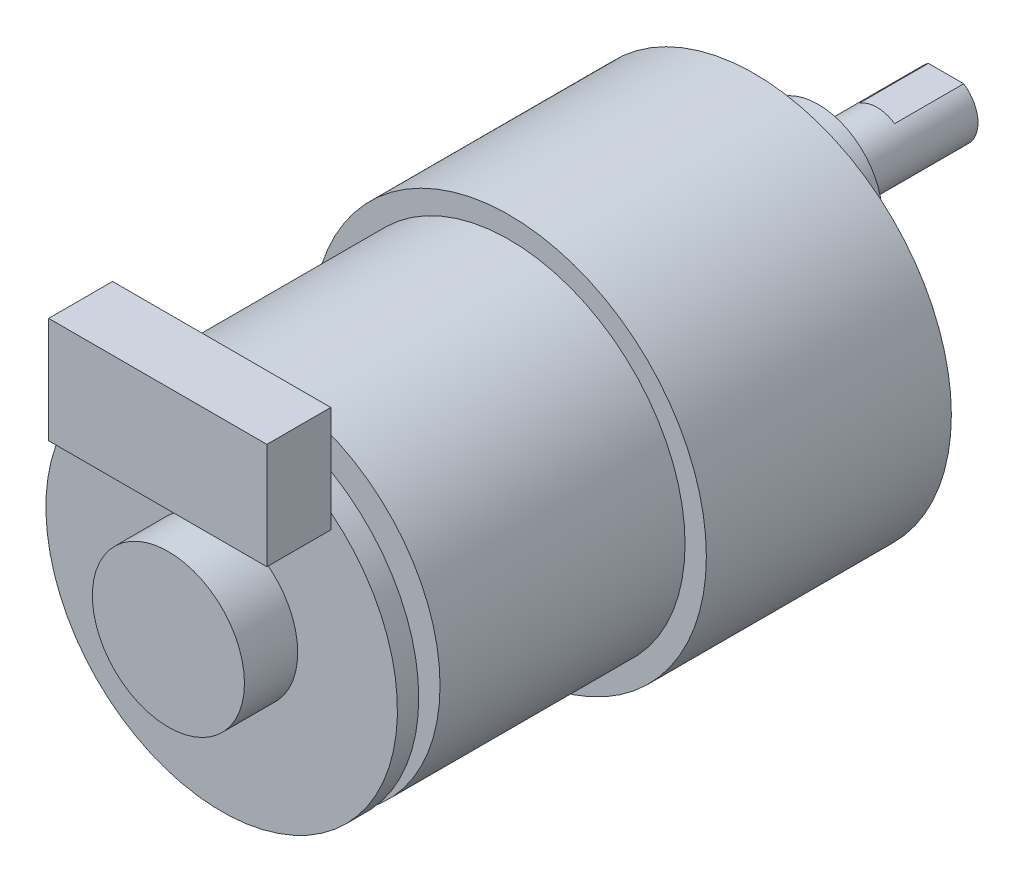
SolidWorks part; units mm, degrees
ref_plane "前视基准面" through (0, 0, 0) normal (0, 0, 1) x (1, 0, 0)
ref_plane "上视基准面" through (0, 0, 0) normal (0, 1, 0) x (1, 0, 0)
ref_plane "右视基准面" through (0, 0, 0) normal (1, 0, 0) x (0, 0, -1)
sketch "草图1" plane through (0, 0, 0) normal (0, 0, 1) x (1, 0, 0)
  circle A0 centre (0, 0) radius 18.5
  dimension "D1" = 37
extrude "凸台-拉伸1" add sketch "草图1" along normal blind 23
sketch "草图2" plane through (0, 0, 23) normal (0, 0, 1) x (1, 0, 0)
  circle A0 centre (0, 0) radius 16.5
  dimension "D1" = 33
extrude "凸台-拉伸2" add sketch "草图2" along normal blind 23
sketch "草图3" plane through (0, 0, 0) normal (0, 0, -1) x (-1, 0, 0)
  line L0 (-20.8009, 0) -> (22.2643, 0) construction
  circle A0 centre (0, 7) radius 6
  dimension "D1" = 12
  dimension "D2" = 7
extrude "凸台-拉伸3" add sketch "草图3" along normal blind 6
sketch "草图4" plane through (0, 0, -6) normal (0, 0, -1) x (-1, 0, 0)
  circle A0 centre (0, 7) radius 3
  dimension "D1" = 6
extrude "凸台-拉伸4" add sketch "草图4" along normal blind 12
sketch "草图5" plane through (0, 0, 0) normal (1, 0, 0) x (0, 0, -1)
  line L0 (6, 4) -> (18, 4) construction
  line L1 (11.5145, 19.9387) -> (20.0304, 19.9387)
  line L2 (11.5145, 19.9387) -> (11.5145, 9.5)
  line L3 (11.5145, 9.5) -> (20.0304, 9.5)
  line L4 (20.0304, 19.9387) -> (20.0304, 9.5)
  line L5 (11.5145, 19.9387) -> (20.0304, 9.5) construction
  line L6 (11.5145, 9.5) -> (20.0304, 19.9387) construction
  point P0 (15.7725, 14.7193)
  dimension "D1" = 5.5
  dimension "D2" = 10.4387
extrude "切除-拉伸1" cut sketch "草图5" against normal through all both and the other way through all
sketch "草图6" plane through (0, 0, 46) normal (0, 0, 1) x (1, 0, 0)
  circle A0 centre (-10, 0) radius 1
  circle A1 centre (10, 0) radius 1
  dimension "D1" = 2
  dimension "D2" = 2
  dimension "D3" = 10
  dimension "D4" = 10
extrude "凸台-拉伸5" add sketch "草图6" along normal blind 2
sketch "草图7" plane through (0, 0, 48) normal (0, 0, 1) x (1, 0, 0)
  circle A0 centre (0, 0) radius 16.5
extrude "凸台-拉伸6" add sketch "草图7" along normal blind 2
sketch "草图8" plane through (0, 0, 50) normal (0, 0, 1) x (1, 0, 0)
  circle A0 centre (0, 0) radius 7.1395
extrude "凸台-拉伸7" add sketch "草图8" along normal blind 5
sketch "草图9" plane through (0, 0, 50) normal (0, 0, 1) x (1, 0, 0)
  line L1 (-10.2437, 21.4759) -> (10.2437, 21.4759)
  line L2 (-10.2437, 21.4759) -> (-10.2437, 11.5241)
  line L3 (-10.2437, 11.5241) -> (10.2437, 11.5241)
  line L4 (10.2437, 21.4759) -> (10.2437, 11.5241)
  line L5 (-10.2437, 21.4759) -> (10.2437, 11.5241) construction
  line L6 (-10.2437, 11.5241) -> (10.2437, 21.4759) construction
  circle A0 centre (0, 0) radius 16.5 construction
  point P0 (0, 16.5)
extrude "凸台-拉伸8" add sketch "草图9" along normal blind 6
sketch "草图10" plane through (0, 0, 0) normal (0, 0, -1) x (-1, 0, 0)
  circle A0 centre (15.5, 0) radius 1.5
  circle A1 centre (7.75, -13.4234) radius 1.5
  circle A2 centre (-7.75, -13.4234) radius 1.5
  circle A3 centre (-15.5, 0) radius 1.5
  circle A4 centre (-7.75, 13.4234) radius 1.5
  circle A5 centre (7.75, 13.4234) radius 1.5
  point P15 (0, 0)
  dimension "D1" = 3
  dimension "D2" = 15.5
  dimension "D3" = 6
extrude "切除-拉伸2" cut sketch "草图10" against normal blind 2
